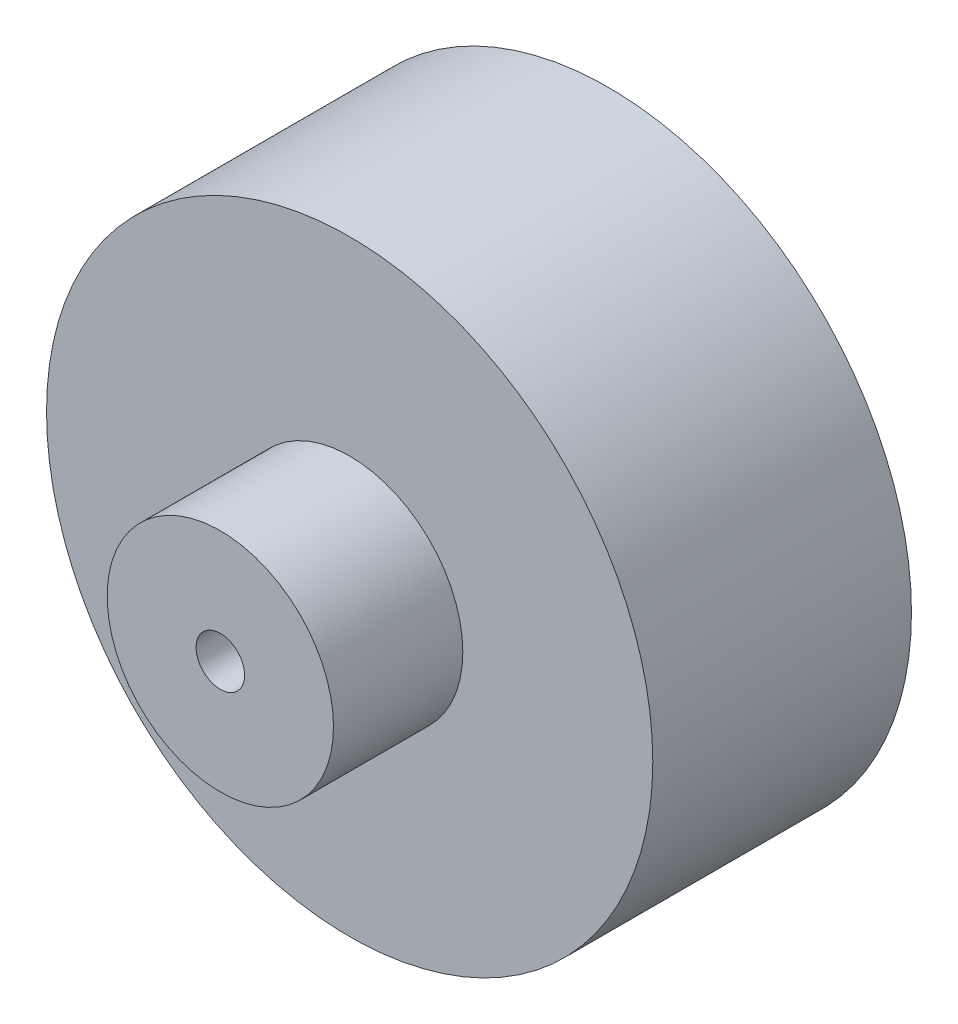
SolidWorks part; units mm, degrees
ref_plane "前视基准面" through (0, 0, 0) normal (0, 0, 1) x (1, 0, 0)
ref_plane "上视基准面" through (0, 0, 0) normal (0, 1, 0) x (1, 0, 0)
ref_plane "右视基准面" through (0, 0, 0) normal (1, 0, 0) x (0, 0, -1)
sketch "Sketch1" plane through (0, 0, 0) normal (0, 0, 1) x (1, 0, 0)
  circle A0 centre (0, 0) radius 37.5
  dimension "D1" = 75
extrude "Boss-Extrude1" add sketch "Sketch1" along normal blind 32
sketch "Sketch2" plane through (0, 0, 32) normal (0, 0, 1) x (1, 0, 0)
  circle A0 centre (0, 0) radius 14
  circle A1 centre (0, 0) radius 3
  dimension "D1" = 28
  dimension "D2" = 6
extrude "Boss-Extrude2" add sketch "Sketch2" along normal blind 16
